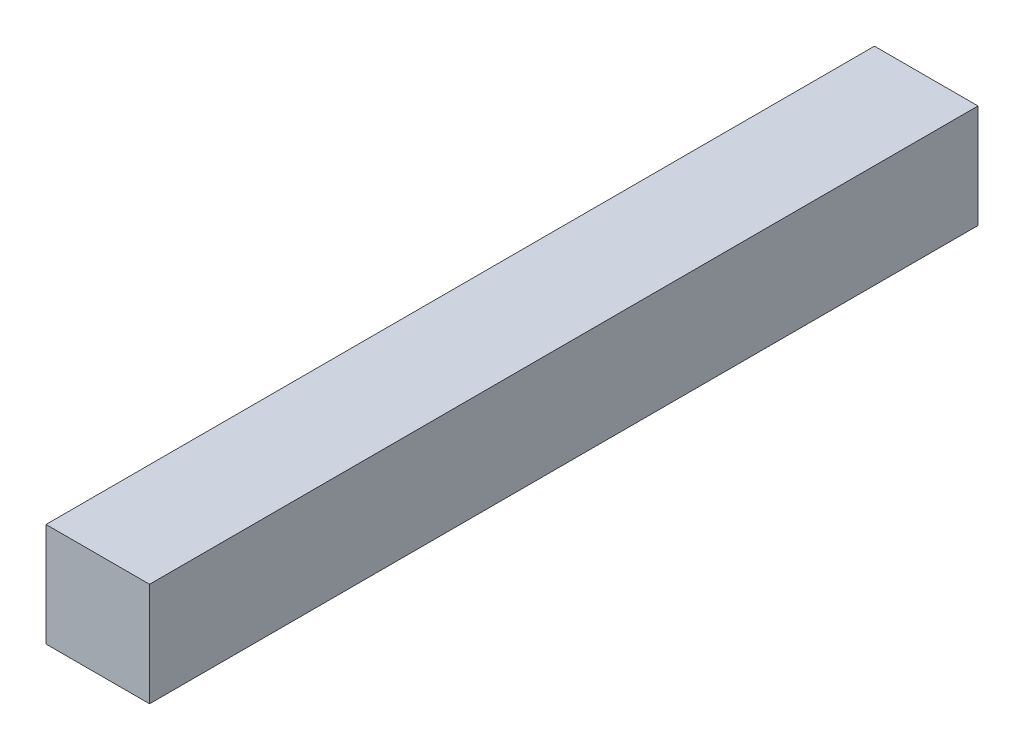
SolidWorks part; units mm, degrees
ref_plane "Front" through (0, 0, 0) normal (0, 0, 1) x (1, 0, 0)
ref_plane "Top" through (0, 0, 0) normal (0, 1, 0) x (1, 0, 0)
ref_plane "Right" through (0, 0, 0) normal (1, 0, 0) x (0, 0, -1)
other "Configuration Table"
sketch "Sketch1" plane through (0, 0, 0) normal (0, 0, 1) x (1, 0, 0)
  line L1 (0, 0) -> (25.4, 0)
  line L2 (0, 0) -> (0, 25.4)
  line L3 (0, 25.4) -> (25.4, 25.4)
  line L4 (25.4, 0) -> (25.4, 25.4)
  dimension "D1" = 25.4
  dimension "D2" = 25.4
extrude "Extrude1" add sketch "Sketch1" along normal blind 203.2
